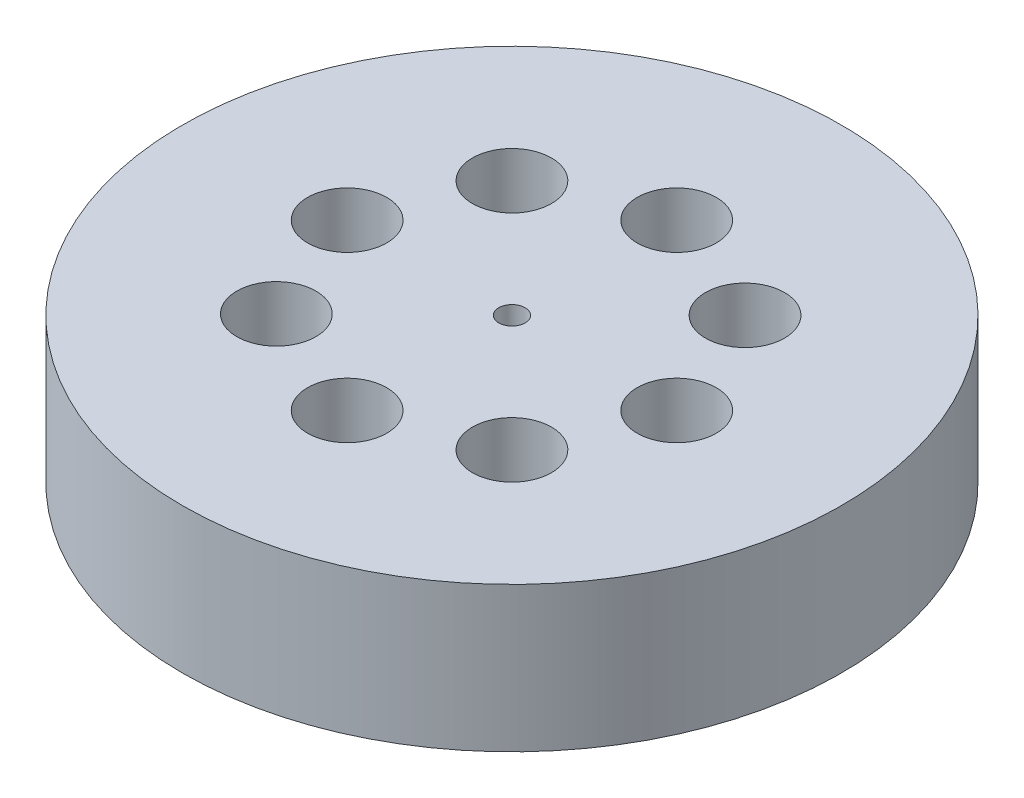
SolidWorks part; units mm, degrees
other "Marquage1"
sketch "Esquisse18" plane through (-50, 0, -50) normal (-0.0591, -0.9883, -0.1406) x (0.5566, 0.0843, -0.8265)
ref_plane "Plan de face" through (0, 0, 0) normal (0, 0, 1) x (1, 0, 0)
ref_plane "Plan de dessus" through (0, 0, 0) normal (0, 1, 0) x (1, 0, 0)
ref_plane "Plan de droite" through (0, 0, 0) normal (1, 0, 0) x (0, 0, -1)
sketch "Esquisse1" plane through (0, 0, 0) normal (0, 1, 0) x (1, 0, 0)
  circle A0 centre (0, 0) radius 50
extrude "Boss.-Extru.1" add sketch "Esquisse1" along normal blind 22
sketch "Esquisse5" plane through (0, 0, 0) normal (0, -1, 0) x (-1, 0, 0)
  circle A0 centre (25, 0) radius 6
  circle A1 centre (0, 25) radius 6
  circle A2 centre (-17.68, 17.68) radius 6
  circle A3 centre (17.68, -17.68) radius 6
  circle A4 centre (0, -25) radius 6
  circle A5 centre (-17.68, -17.68) radius 6
  circle A6 centre (17.68, 17.68) radius 6
  circle A7 centre (-25, 0) radius 6
extrude "Enlèv. mat.-Extru.6" cut sketch "Esquisse5" against normal blind 22 contours A2
sketch "Esquisse7" plane through (0, 0, 0) normal (0, -1, 0) x (-1, 0, 0)
  circle A0 centre (18.0581, -17.68) radius 6
extrude "Enlèv. mat.-Extru.7" cut sketch "Esquisse7" against normal blind 22
sketch "Esquisse8" plane through (0, 0, 0) normal (0, -1, 0) x (-1, 0, 0)
  circle A0 centre (17.68, 17.68) radius 6
extrude "Enlèv. mat.-Extru.8" cut sketch "Esquisse8" against normal blind 22
sketch "Esquisse9" plane through (0, 0, 0) normal (0, -1, 0) x (-1, 0, 0)
  circle A0 centre (-17.68, -17.68) radius 6
extrude "Enlèv. mat.-Extru.9" cut sketch "Esquisse9" against normal blind 22
sketch "Esquisse10" plane through (0, 0, 0) normal (0, -1, 0) x (1, 0, 0)
  circle A0 centre (0, 25) radius 6
extrude "Enlèv. mat.-Extru.10" cut sketch "Esquisse10" against normal blind 22
sketch "Esquisse11" plane through (0, 0, 0) normal (0, -1, 0) x (-1, 0, 0)
  circle A0 centre (25, 0) radius 6
extrude "Enlèv. mat.-Extru.11" cut sketch "Esquisse11" against normal blind 22
sketch "Esquisse12" plane through (0, 0, 0) normal (0, -1, 0) x (-1, 0, 0)
  circle A0 centre (-25, 0) radius 6
extrude "Enlèv. mat.-Extru.12" cut sketch "Esquisse12" against normal blind 22
sketch "Esquisse13" plane through (0, 0, 0) normal (0, -1, 0) x (-1, 0, 0)
  circle A0 centre (0, 25) radius 6
extrude "Enlèv. mat.-Extru.13" cut sketch "Esquisse13" against normal blind 22
sketch "Esquisse14" plane through (0, 0, 0) normal (0, -1, 0) x (-1, 0, 0)
  circle A0 centre (0, 0) radius 10
extrude "Enlèv. mat.-Extru.15" cut sketch "Esquisse14" against normal blind 18
sketch "Esquisse15" plane through (0, 18, 0) normal (0, -1, 0) x (-1, 0, 0)
  circle A0 centre (0, 0) radius 2
extrude "Enlèv. mat.-Extru.16" cut sketch "Esquisse15" against normal blind 4
